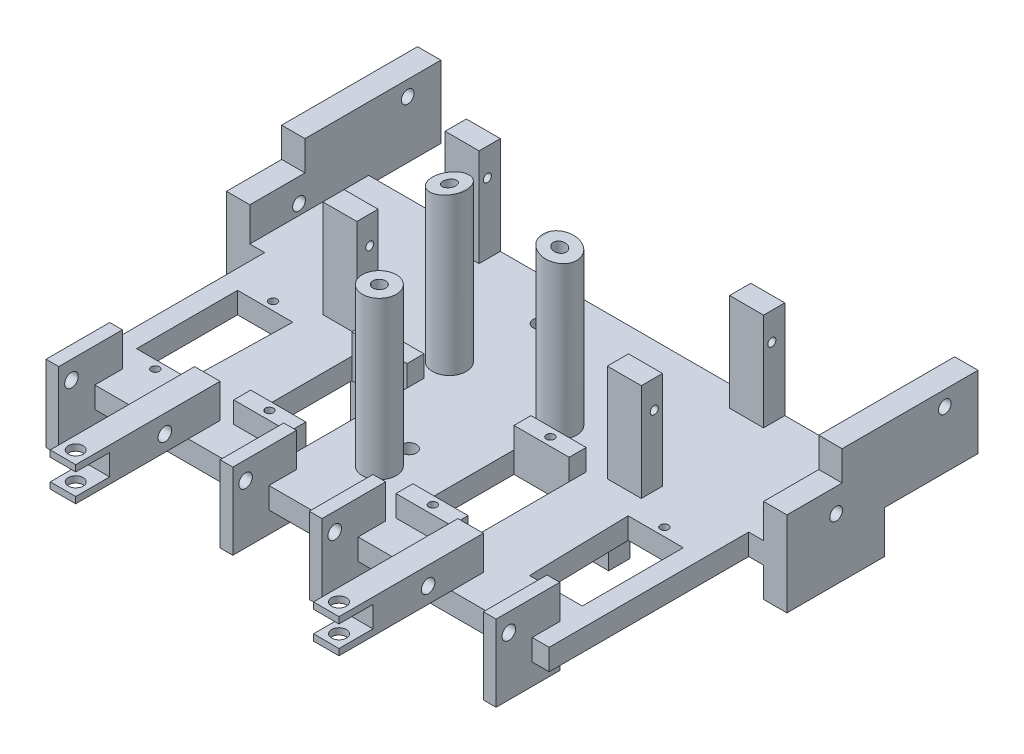
SolidWorks part; units mm, degrees
material "PMMA"
ref_plane "前视基准面" through (0, 0, 0) normal (0, 0, 1) x (1, 0, 0)
ref_plane "上视基准面" through (0, 0, 0) normal (0, 1, 0) x (1, 0, 0)
ref_plane "右视基准面" through (0, 0, 0) normal (1, 0, 0) x (0, 0, -1)
sketch "草图1" plane through (0, 0, 0) normal (0, 1, 0) x (1, 0, 0)
  line L1 (-57, 37.5) -> (57, 37.5)
  line L2 (-57, 37.5) -> (-57, -37.5)
  line L3 (-57, -37.5) -> (57, -37.5)
  line L4 (57, 37.5) -> (57, -37.5)
  line L5 (-57, 37.5) -> (57, -37.5) construction
  line L6 (-57, -37.5) -> (57, 37.5) construction
  point P0 (0, 0)
  dimension "D1" = 114
  dimension "D2" = 75
extrude "凸台-拉伸1" add sketch "草图1" along normal blind 5
sketch "草图4" plane through (0, 5, 0) normal (0, 1, 0) x (1, 0, 0)
  line L1 (-60.5, 9.5) -> (60.5, 9.5)
  line L2 (-60.5, 9.5) -> (-60.5, 37.5)
  line L3 (-60.5, 37.5) -> (60.5, 37.5)
  line L4 (60.5, 9.5) -> (60.5, 37.5)
  line L5 (-60.5, 9.5) -> (60.5, 37.5) construction
  line L6 (-60.5, 37.5) -> (60.5, 9.5) construction
  line L7 (-57, -37.5) -> (57, -37.5) construction
  point P0 (0, 23.5)
  dimension "D1" = 121
  dimension "D2" = 28
  dimension "D3" = 75
extrude "凸台-拉伸4" add sketch "草图4" against normal blind 5
sketch "草图5" plane through (-60.5, 0, 0) normal (-1, 0, 0) x (0, 0, 1)
  line L0 (-37.5, 5) -> (-9.5, 5) construction
  line L1 (-9.5, 13) -> (-32.5, 13)
  line L2 (-9.5, 13) -> (-9.5, -7)
  line L3 (-9.5, -7) -> (-32.5, -7)
  line L4 (-32.5, 13) -> (-32.5, -7)
  line L5 (-9.5, 5) -> (-9.5, 0) construction
  dimension "D1" = 8
  dimension "D2" = 23
  dimension "D3" = 20
extrude "凸台-拉伸5" add sketch "草图5" along normal blind 5.5
sketch "草图18" plane through (0, 0, 0) normal (0, -1, 0) x (1, 0, 0)
  line L0 (-66, -32.5) -> (-60.5, -32.5) construction
  line L1 (-60.5, -9.5) -> (-54, -9.5)
  line L2 (-60.5, -9.5) -> (-60.5, -32.5)
  line L3 (-60.5, -32.5) -> (-54, -32.5)
  line L4 (-54, -9.5) -> (-54, -32.5)
  line L5 (-66, -32.5) -> (-66, -9.5) construction
  dimension "D1" = 12
sketch "草图6" plane through (-60.5, 0, 0) normal (-1, 0, 0) x (0, 0, 1)
  line L1 (-54.5, 20) -> (-22.5, 20)
  line L2 (-54.5, 20) -> (-54.5, 3)
  line L3 (-54.5, 3) -> (-22.5, 3)
  line L4 (-22.5, 20) -> (-22.5, 3)
  line L5 (-37.5, 5) -> (-32.5, 5) construction
  line L6 (-37.5, 0) -> (-37.5, 5) construction
  dimension "D1" = 15
  dimension "D2" = 17
  dimension "D3" = 32
  dimension "D4" = 17
extrude "凸台-拉伸6" add sketch "草图6" along normal blind 5.5
sketch "草图8" plane through (0, 5, 0) normal (0, 1, 0) x (1, 0, 0)
  line L0 (60.5, 37.5) -> (-60.5, 37.5) construction
  line L1 (-37.5, 37.5) -> (-29.5, 37.5)
  line L2 (-37.5, 37.5) -> (-37.5, 32.5)
  line L3 (-37.5, 32.5) -> (-29.5, 32.5)
  line L4 (-29.5, 37.5) -> (-29.5, 32.5)
  line L6 (-37.5, 8.7) -> (-29.5, 8.7)
  line L7 (-37.5, 8.7) -> (-37.5, 3.7)
  line L8 (-37.5, 3.7) -> (-29.5, 3.7)
  line L9 (-29.5, 8.7) -> (-29.5, 3.7)
  dimension "D1" = 23.8
  dimension "D2" = 37.5
  dimension "D3" = 8
  dimension "D4" = 5
  dimension "D5" = 5
extrude "凸台-拉伸7" add sketch "草图8" along normal blind 23
sketch "草图9" plane through (0, 5, 0) normal (0, 1, 0) x (1, 0, 0)
  line L1 (-12, -31) -> (-9, -31)
  line L2 (-12, -31) -> (-12, -46)
  line L3 (-12, -46) -> (-9, -46)
  line L4 (-9, -31) -> (-9, -46)
  dimension "D1" = 12
  dimension "D2" = 3
  dimension "D3" = 15
  dimension "D4" = 46
extrude "凸台-拉伸8" add sketch "草图9" along normal blind 8 and the other way blind 10
sketch "草图10" plane through (0, 5, 0) normal (0, 1, 0) x (1, 0, 0)
  line L0 (-12, -31) -> (-12, -46) construction
  line L1 (-53, -31) -> (-50, -31)
  line L2 (-53, -31) -> (-53, -46)
  line L3 (-53, -46) -> (-50, -46)
  line L4 (-50, -31) -> (-50, -46)
  line L6 (-9, -31) -> (-12, -31) construction
  line L7 (-12, -46) -> (-9, -46) construction
  dimension "D1" = 38
extrude "凸台-拉伸9" add sketch "草图10" along normal blind 8 and the other way blind 10
sketch "草图11" plane through (0, 5, 0) normal (0, 1, 0) x (1, 0, 0)
  line L1 (-34, -30) -> (-28, -30)
  line L2 (-34, -30) -> (-34, -64)
  line L3 (-34, -64) -> (-28, -64)
  line L4 (-28, -30) -> (-28, -64)
  dimension "D1" = 6
  dimension "D2" = 34
  dimension "D3" = 64
  dimension "D4" = 28
extrude "凸台-拉伸10" add sketch "草图11" along normal blind 8
sketch "草图12" plane through (0, 5, 0) normal (0, 1, 0) x (1, 0, 0)
  circle A0 centre (-13, 9) radius 4
  dimension "D1" = 13
  dimension "D2" = 9
  dimension "D3" = 8
extrude "凸台-拉伸11" add sketch "草图12" along normal blind 37
sketch "草图19" plane through (-37.5, 0, 0) normal (-1, 0, 0) x (0, 0, 1)
  line L1 (-8.7, 28) -> (-8.7, 5) construction
  line L2 (-8.7, 28) -> (-3.7, 28) construction
  line L3 (-32.5, 28) -> (-32.5, 5) construction
  circle A0 centre (-6.75, 21.5) radius 0.95
  circle A1 centre (-34.45, 21.5) radius 0.95
  dimension "D1" = 6.5
  dimension "D2" = 1.95
  dimension "D3" = 1.9
  dimension "D4" = 27.7
  dimension "D5" = 1.9
  dimension "D6" = 1.95
extrude "切除-拉伸8" cut sketch "草图19" against normal up to next
sketch "草图25" plane through (0, 5, 0) normal (0, 1, 0) x (1, 0, 0)
  circle A0 centre (0, -20.5) radius 4
  circle A1 centre (-13, 9) radius 4 construction
  dimension "D1" = 20.5
extrude "凸台-拉伸14" add sketch "草图25" along normal blind 37
sketch "草图26" plane through (0, 0, 0) normal (0, 0, 1) x (1, 0, 0)
  line L0 (-17, 42) -> (-17, 40.644)
  line L1 (-17, 42) -> (-17, 5) construction
  line L2 (-17, 40.644) -> (-9.31, 42)
  line L3 (-9, 42) -> (-17, 42) construction
  line L4 (-9.31, 42) -> (-17, 42)
  dimension "D1" = 10
  dimension "D2" = 0.31
extrude "切除-拉伸14" cut sketch "草图26" against normal blind 36
sketch "草图28" plane through (0, 0, 64) normal (0, 0, 1) x (1, 0, 0)
  line L0 (-34, 13) -> (-34, 5) construction
  line L1 (-34, 11.5) -> (-28, 11.5)
  line L2 (-34, 11.5) -> (-34, 6.5)
  line L3 (-34, 6.5) -> (-28, 6.5)
  line L4 (-28, 11.5) -> (-28, 6.5)
  line L5 (-28, 13) -> (-28, 5) construction
  line L6 (-34, 13) -> (-28, 13) construction
  dimension "D1" = 1.5
  dimension "D2" = 5
extrude "切除-拉伸16" cut sketch "草图28" against normal blind 8
sketch "草图29" plane through (0, 13, 0) normal (0, 1, 0) x (1, 0, 0)
  line L0 (-34, -64) -> (-28, -64) construction
  circle A0 centre (-31, -61) radius 1.75
  point P5 (-31, -64)
  dimension "D1" = 3
  dimension "D2" = 3.5
extrude "切除-拉伸17" cut sketch "草图29" against normal blind 8
sketch "草图30" plane through (-53, 0, 0) normal (-1, 0, 0) x (0, 0, 1)
  line L0 (31, 5) -> (37.5, 5) construction
  circle A0 centre (43, 8.75) radius 1.6
  dimension "D1" = 43
  dimension "D2" = 3.75
  dimension "D3" = 3.2
extrude "切除-拉伸18" cut sketch "草图30" against normal blind 48
sketch "草图31" plane through (0, 5, 0) normal (0, 1, 0) x (1, 0, 0)
  circle A0 centre (0, -13.5) radius 1.75
  circle A1 centre (-10, 27.5) radius 1.75
  circle A2 centre (10, 27.5) radius 1.75
  dimension "D1" = 20
  dimension "D2" = 10
  dimension "D3" = 27.5
  dimension "D4" = 3.5
  dimension "D5" = 3.5
  dimension "D7" = 3.5
  dimension "D6" = 13.5
extrude "切除-拉伸19" cut sketch "草图31" against normal blind 20
sketch "草图34" plane through (-53, 0, 0) normal (-1, 0, 0) x (0, 0, 1)
  line L0 (46, -5) -> (46, 13) construction
  line L1 (46, 5) -> (43, 5)
  line L2 (46, 5) -> (46, -5)
  line L3 (46, -5) -> (43, -5)
  line L4 (43, 5) -> (43, -5)
  line L5 (37.5, 5) -> (64, 5) construction
  line L6 (31, -5) -> (46, -5) construction
  dimension "D1" = 3
sketch "草图35" plane through (-66, 0, 0) normal (-1, 0, 0) x (0, 0, 1)
  circle A0 centre (-46.6884, 16.4527) radius 1.5
  circle A1 centre (-21.0894, 7.4378) radius 1.5
  dimension "D1" = 3
  dimension "D2" = 3
extrude "切除-拉伸23" cut sketch "草图35" against normal blind 15
sketch "草图36" plane through (0, 5, 0) normal (0, 1, 0) x (1, 0, 0)
  line L0 (-19.2359, 3.8223) -> (-19.2359, -28.2182) construction
  line L1 (-25.601, -1.3876) -> (-12.601, -1.3876)
  line L2 (-25.601, -1.3876) -> (-25.601, -25.1876)
  line L3 (-25.601, -25.1876) -> (-12.601, -25.1876)
  line L4 (-12.601, -1.3876) -> (-12.601, -25.1876)
  line L5 (-39.4915, -1.3876) -> (-40.0537, -25.1876)
  line L6 (-47.6088, 4.4682) -> (-47.6088, -27.5723) construction
  line L7 (-52.4915, -25.1876) -> (-40.0537, -25.1876)
  line L8 (-52.4915, -1.3876) -> (-52.4915, -25.1876)
  line L9 (-52.4915, -1.3876) -> (-39.4915, -1.3876)
  circle A0 centre (-19.2359, 0.5624) radius 0.95
  circle A1 centre (-19.2359, -27.1376) radius 0.95
  circle A2 centre (-46.1265, -27.1376) radius 0.95
  circle A3 centre (-46.0774, 0.5624) radius 0.95
  dimension "D3" = 1.9
  dimension "D4" = 1.9
  dimension "D9" = 1.9
  dimension "D10" = 1.9
  dimension "D1" = 23.8
  dimension "D2" = 13
  dimension "D5" = 1.95
  dimension "D6" = 1.95
  dimension "D7" = 23.8
  dimension "D8" = 13
  dimension "D11" = 1.95
  dimension "D12" = 1.95
extrude "切除-拉伸24" cut sketch "草图36" against normal blind 7
sketch "草图37" plane through (0, 0, 0) normal (0, -1, 0) x (1, 0, 0)
  line L1 (-25.1215, -36.8982) -> (-31.1215, -36.8982)
  line L2 (-25.1215, -36.8982) -> (-25.1215, -31.8982)
  line L3 (-25.1215, -31.8982) -> (-31.1215, -31.8982)
  line L4 (-31.1215, -36.8982) -> (-31.1215, -31.8982)
  line L5 (-25.1215, -8.0982) -> (-30.4279, -8.0982)
  line L6 (-25.1215, -8.0982) -> (-25.1215, -3.0982)
  line L7 (-25.1215, -3.0982) -> (-30.4279, -3.0982)
  line L8 (-30.4279, -8.0982) -> (-30.4279, -3.0982)
  dimension "D1" = 23.8
  dimension "D2" = 6
  dimension "D3" = 5
  dimension "D4" = 5
extrude "凸台-拉伸15" add sketch "草图37" along normal blind 13
sketch "草图38" plane through (-31.1215, 0, 0) normal (-1, 0, 0) x (0, 0, 1)
  line L0 (-31.8982, -13) -> (-31.8982, 0) construction
  line L2 (-37.5, 0) -> (-32.5, 0) construction
  line L3 (-19.9982, 2.1642) -> (-19.9982, -15.8009) construction
  circle A0 centre (-33.8482, -4.5) radius 0.95
  circle A1 centre (-6.1482, -4.5) radius 0.95
  dimension "D1" = 1.9
  dimension "D2" = 1.95
  dimension "D3" = 4.5
  dimension "D4" = 11.9
extrude "切除-拉伸25" cut sketch "草图38" against normal blind 13
sketch "草图43" plane through (0, 0, 0) normal (0, -1, 0) x (1, 0, 0)
  line L0 (60.5, -37.5) -> (-60.5, -37.5) construction
  line L1 (-50.4279, -1.0982) -> (-17.1215, -1.0982)
  line L2 (-50.4279, -1.0982) -> (-50.4279, -37.5)
  line L3 (-50.4279, -37.5) -> (-17.1215, -37.5)
  line L4 (-17.1215, -1.0982) -> (-17.1215, -37.5)
  line L5 (-25.1215, -3.0982) -> (-30.4279, -3.0982) construction
  line L6 (-25.1215, -8.0982) -> (-25.1215, -3.0982) construction
  line L7 (-25.1215, -3.0982) -> (-30.4279, -3.0982) construction
  line L8 (-30.4279, -3.0982) -> (-30.4279, -8.0982) construction
  line L9 (-30.4279, -8.0982) -> (-25.1215, -8.0982) construction
  line L10 (-25.1215, -36.8982) -> (-25.1215, -31.8982) construction
  line L11 (-25.1215, -31.8982) -> (-31.1215, -31.8982) construction
  line L12 (-31.1215, -31.8982) -> (-31.1215, -36.8982) construction
  line L13 (-31.1215, -36.8982) -> (-25.1215, -36.8982) construction
  line L14 (-25.1215, -8.0982) -> (-25.1215, -3.0982)
  line L15 (-25.1215, -3.0982) -> (-30.4279, -3.0982)
  line L16 (-30.4279, -3.0982) -> (-30.4279, -8.0982)
  line L17 (-30.4279, -8.0982) -> (-25.1215, -8.0982)
  line L18 (-25.1215, -36.8982) -> (-25.1215, -31.8982)
  line L19 (-25.1215, -31.8982) -> (-31.1215, -31.8982)
  line L20 (-31.1215, -31.8982) -> (-31.1215, -36.8982)
  line L21 (-31.1215, -36.8982) -> (-25.1215, -36.8982)
  dimension "D1" = 2
  dimension "D2" = 8
  dimension "D3" = 20
extrude "切除-拉伸28" cut sketch "草图43" against normal blind 2
sketch "草图41" plane through (0, 5, 0) normal (0, 1, 0) x (1, 0, 0)
  line L0 (-25.601, -1.3876) -> (-25.601, -25.1876) construction
  line L1 (-12.601, -1.3876) -> (-25.601, -1.3876)
  line L2 (-12.601, -1.3876) -> (-12.601, 2.6124)
  line L3 (-12.601, 2.6124) -> (-25.601, 2.6124)
  line L4 (-25.601, -1.3876) -> (-25.601, 2.6124)
  line L5 (-12.601, -25.1876) -> (-12.601, -1.3876) construction
  line L6 (-25.601, -25.1876) -> (-12.601, -25.1876)
  line L7 (-25.601, -25.1876) -> (-25.601, -29.1876)
  line L8 (-25.601, -29.1876) -> (-12.601, -29.1876)
  line L9 (-12.601, -25.1876) -> (-12.601, -29.1876)
  circle A0 centre (-19.2359, 0.5624) radius 0.95
  circle A1 centre (-19.2359, -27.1376) radius 0.95
  dimension "D3" = 1.9
  dimension "D4" = 1.9
  dimension "D1" = 4
  dimension "D2" = 4
extrude "凸台-拉伸16" add sketch "草图41" along normal blind 5
sketch "草图39" plane through (0, 5, 0) normal (0, 1, 0) x (1, 0, 0)
  circle A0 centre (-13, 9) radius 1.5
  circle A1 centre (0, -20.5) radius 1.5
  dimension "D1" = 3
  dimension "D2" = 3
extrude "切除-拉伸26" cut sketch "草图39" against normal blind 13 and the other way blind 42
mirror "镜向1" about plane through (0, 0, 0) normal (1, 0, 0) of "凸台-拉伸5", "凸台-拉伸6", "凸台-拉伸7", "凸台-拉伸8", "凸台-拉伸9", "凸台-拉伸10", "凸台-拉伸11", "切除-拉伸8", "切除-拉伸14", "切除-拉伸16", "切除-拉伸17", "切除-拉伸18", "切除-拉伸23", "切除-拉伸24", "凸台-拉伸15", "切除-拉伸25", "切除-拉伸28", "凸台-拉伸16", "切除-拉伸26"
